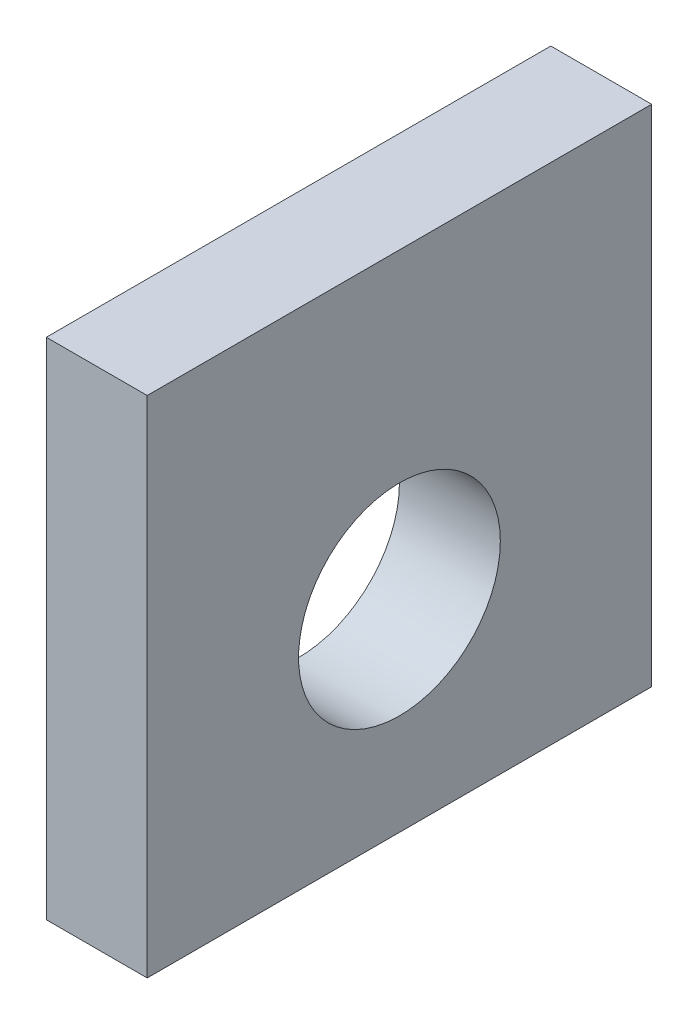
SolidWorks part; units mm, degrees
ref_plane "Front Plane" through (0, 0, 0) normal (0, 0, 1) x (1, 0, 0)
ref_plane "Top Plane" through (0, 0, 0) normal (0, 1, 0) x (1, 0, 0)
ref_plane "Right Plane" through (0, 0, 0) normal (1, 0, 0) x (0, 0, -1)
sketch "Sketch1" plane through (0, 0, 0) normal (1, 0, 0) x (0, 0, -1)
  line L1 (-7.9375, 7.9375) -> (7.9375, 7.9375)
  line L2 (-7.9375, 7.9375) -> (-7.9375, -7.9375)
  line L3 (-7.9375, -7.9375) -> (7.9375, -7.9375)
  line L4 (7.9375, 7.9375) -> (7.9375, -7.9375)
  dimension "D1" = 15.875
  dimension "D2" = 7.9375
  dimension "D3" = 15.875
  dimension "D4" = 7.9375
extrude "Boss-Extrude1" add sketch "Sketch1" along normal blind 3.175
sketch "Sketch2" plane through (3.175, 0, 0) normal (1, 0, 0) x (0, 0, -1)
  line L0 (-7.9375, -7.9375) -> (7.9375, -7.9375) construction
  circle A0 centre (0, -1.5875) radius 3.175
  dimension "D1" = 6.35
  dimension "D2" = 6.35
extrude "Cut-Extrude1" cut sketch "Sketch2" against normal up to next
